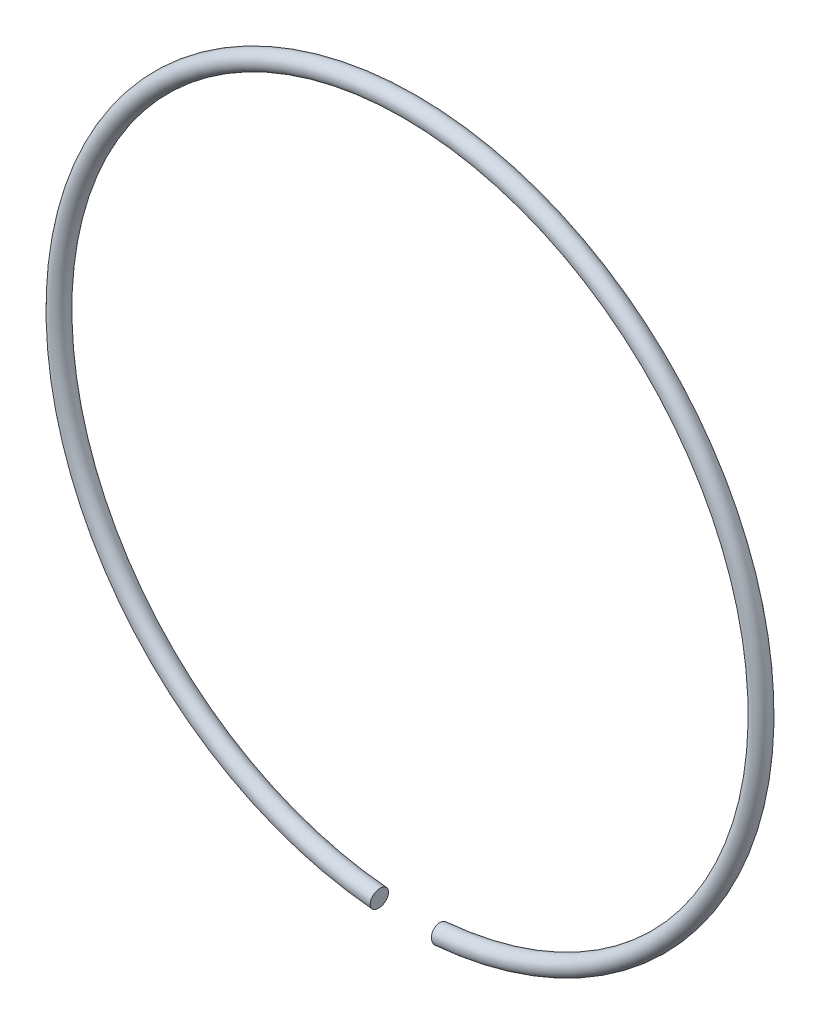
SolidWorks part; units mm, degrees
ref_plane "Front Plane" through (0, 0, 0) normal (0, 0, 1) x (1, 0, 0)
ref_plane "Top Plane" through (0, 0, 0) normal (0, 1, 0) x (1, 0, 0)
ref_plane "Right Plane" through (0, 0, 0) normal (1, 0, 0) x (0, 0, -1)
sketch "Layout" plane through (0, 0, 0) normal (0, 0, 1) x (1, 0, 0)
  circle A0 centre (0, 0) radius 97 construction
  circle A1 centre (0, 0) radius 57.5 construction
  dimension "D1" = 194
  dimension "D2" = 115
sketch "Sketch1" plane through (0, 0, 0) normal (1, 0, 0) x (0, 0, -1)
  line L0 (0, 0) -> (0, 57.5) construction
  line L1 (0, 97) -> (0, -97) construction
  line L2 (0, 0) -> (50, 0) construction
  circle A0 centre (0, 57.5) radius 1.5
  dimension "D2" = 3
  dimension "D1" = 115
  dimension "D3" = 50
revolve "Revolve1" add sketch "Sketch1" angle 350 mid plane about L2
sketch "Geometry for Assembly Mate" plane through (0, 0, 0) normal (1, 0, 0) x (0, 0, -1)
  circle A0 centre (0, 57.5) radius 25 construction
  dimension "D1" = 50
  dimension "D2" = 57.5
equation "\"Clutch Plate OD\"= 194"
equation "\"Clutch Plate ID\"= 125"
equation "\"Spring Housing OD\"= 115"
equation "\"d\"= 1"
equation "\"e\"= 1"
equation "\"x\"= 1"
equation "\"y\"= 1"
equation "\"z\"= 1"
equation "\"D1@Layout\" = \"Clutch Plate OD\""
equation "\"D2@Layout\"=\"Spring Housing OD\""
